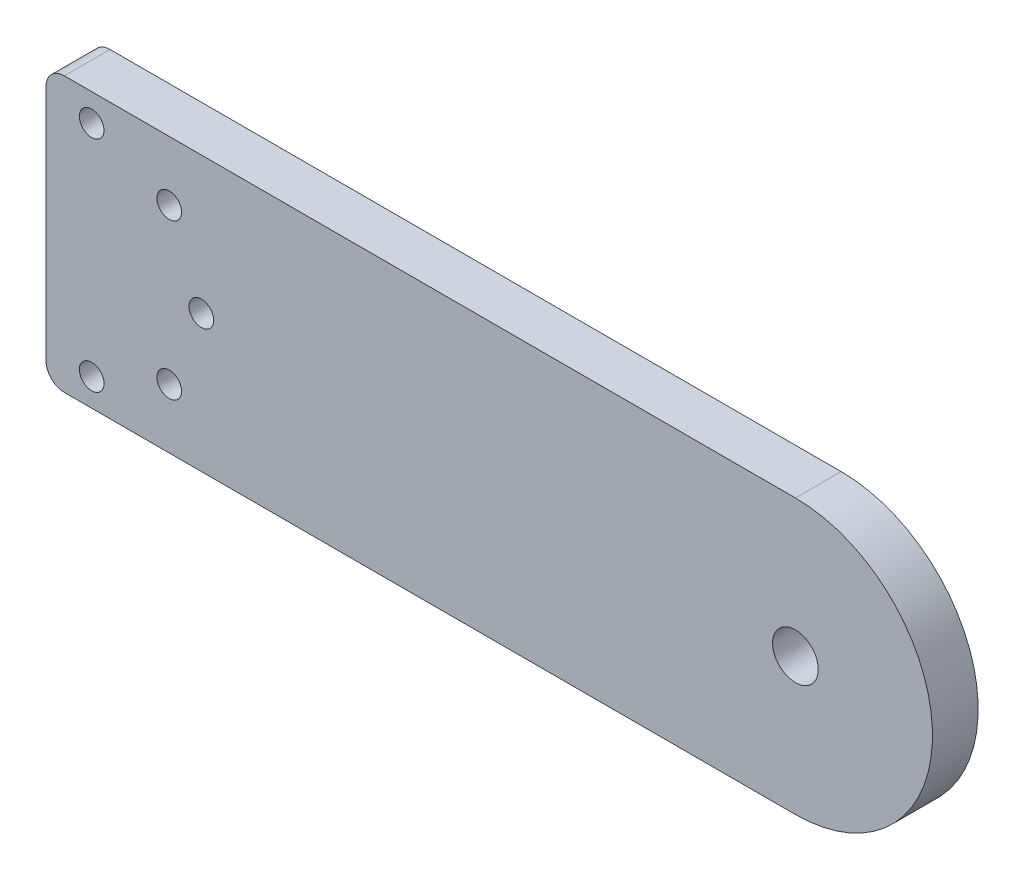
SolidWorks part; units mm, degrees
ref_plane "前视基准面" through (0, 0, 0) normal (0, 0, 1) x (1, 0, 0)
ref_plane "上视基准面" through (0, 0, 0) normal (0, 1, 0) x (1, 0, 0)
ref_plane "右视基准面" through (0, 0, 0) normal (1, 0, 0) x (0, 0, -1)
other "Configuration Table"
sketch "草图1" plane through (0, 0, 0) normal (0, 0, 1) x (1, 0, 0)
  line L1 (-38, 15) -> (-8.7442, 15) construction
  line L8 (-40, 13) -> (-40, -13)
  line L10 (42, -15) -> (-38, -15)
  line L11 (-40, -8.25) -> (-40, -13) construction
  line L13 (42, 15) -> (-38, 15)
  circle A0 centre (-35, -12) radius 1.35 construction
  circle A1 centre (-26.5147, -8.4853) radius 1.35 construction
  circle A2 centre (-35, 12) radius 1.35 construction
  circle A3 centre (-26.5147, 8.4853) radius 1.35 construction
  circle A4 centre (-23, 0) radius 1.35 construction
  circle A5 centre (-35, -12) radius 1.35
  circle A6 centre (-26.5147, -8.4853) radius 1.35
  circle A7 centre (-35, 12) radius 1.35
  circle A8 centre (-26.5147, 8.4853) radius 1.35
  circle A9 centre (-23, 0) radius 1.35
  arc A10 (42, 15) -> (42, -15) centre (42, 0) cw
  arc A11 (-38, 15) -> (-40, 13) centre (-38, 13) ccw
  arc A13 (-40, -13) -> (-38, -15) centre (-38, -13) ccw
  circle A14 centre (42, 0) radius 2.5
  dimension "D2" = 2
  dimension "D4" = 5
  dimension "D1" = 30
  dimension "D3" = 80
extrude "凸台-拉伸1" add sketch "草图1" along normal blind 5
